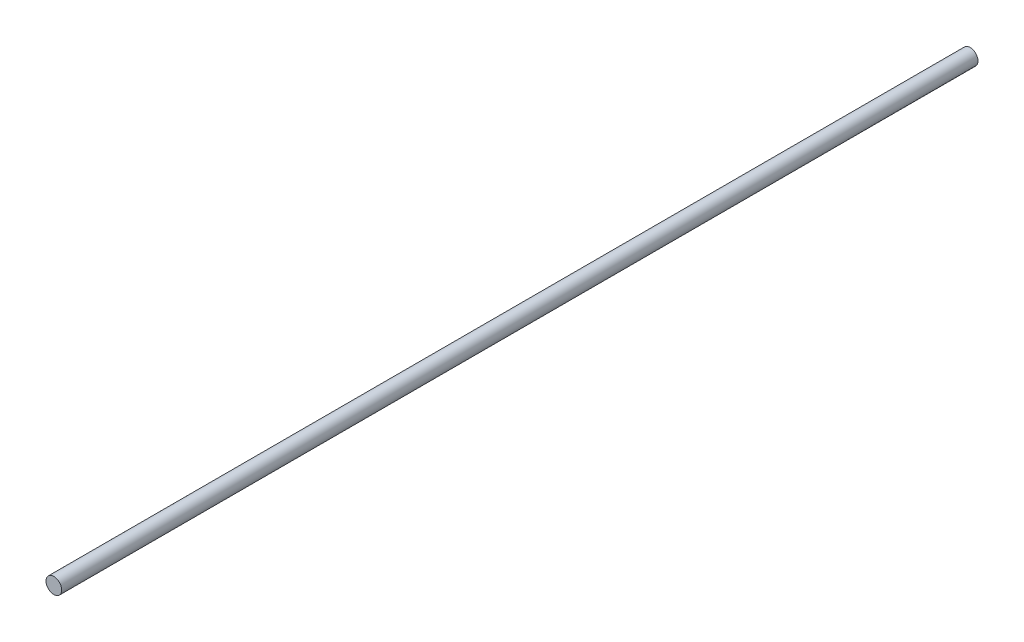
SolidWorks part; units mm, degrees
ref_plane "Front Plane" through (0, 0, 0) normal (0, 0, 1) x (1, 0, 0)
ref_plane "Top Plane" through (0, 0, 0) normal (0, 1, 0) x (1, 0, 0)
ref_plane "Right Plane" through (0, 0, 0) normal (1, 0, 0) x (0, 0, -1)
sketch "Esquisse1" plane through (0, 0, 0) normal (0, 0, 1) x (1, 0, 0)
  circle A0 centre (0, 0) radius 3
  dimension "D1" = 6
extrude "Boss.-Extru.1" add sketch "Esquisse1" along normal blind 350
